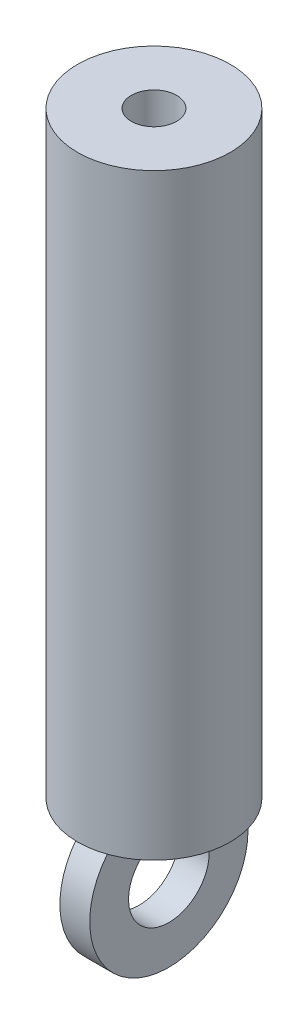
SolidWorks part; units mm, degrees
ref_plane "Front Plane" through (0, 0, 0) normal (0, 0, 1) x (1, 0, 0)
ref_plane "Top Plane" through (0, 0, 0) normal (0, 1, 0) x (1, 0, 0)
ref_plane "Right Plane" through (0, 0, 0) normal (1, 0, 0) x (0, 0, -1)
sketch "Sketch1" plane through (0, 0, 0) normal (0, 1, 0) x (1, 0, 0)
  circle A0 centre (0, 0) radius 4.5466
  circle A1 centre (0, 0) radius 1.3462
  dimension "D1" = 9.0932
  dimension "D2" = 2.6924
extrude "Extrude1" add sketch "Sketch1" along normal blind 35.56 from offset 1.27
sketch "Sketch4" plane through (0, 0, 0) normal (1, 0, 0) x (0, 0, -1)
  line L0 (4.5466, 36.83) -> (-4.5466, 36.83) construction
  line L2 (0, -2.3114) -> (0, 67.6656) construction
  circle A0 centre (0, -2.3114) radius 4.7117
  circle A1 centre (0, -2.3114) radius 2.4003
  dimension "D1" = 39.1414
  dimension "D2" = 9.4234
  dimension "D3" = 4.8006
extrude "Extrude2" add sketch "Sketch4" along normal mid plane 1.778 separate body
